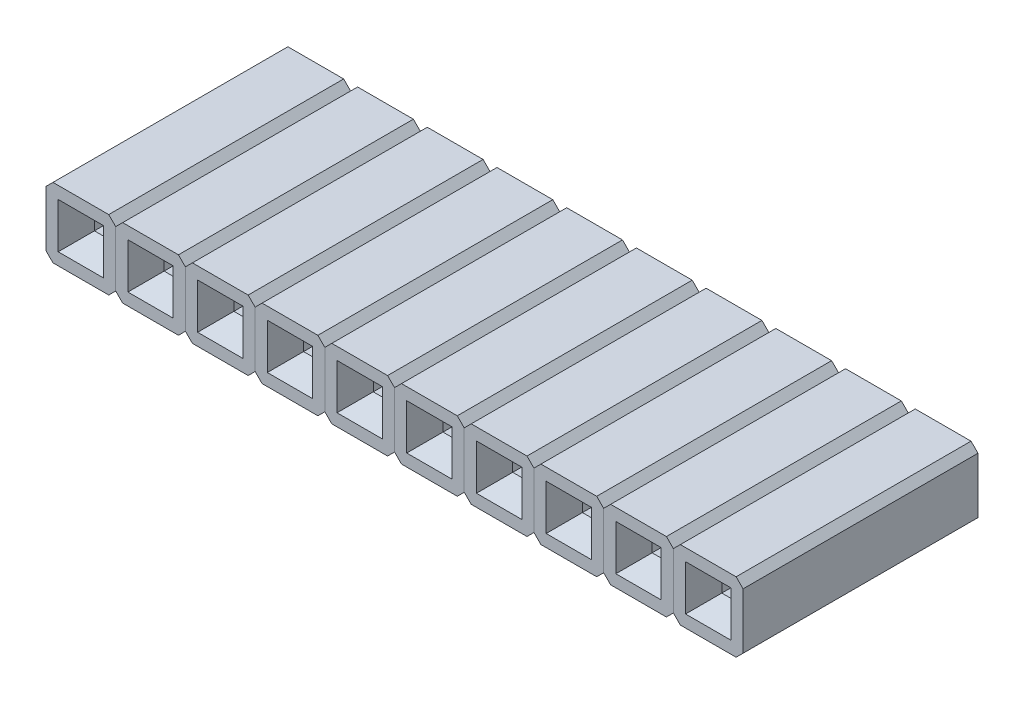
SolidWorks part; units mm, degrees
ref_plane "Front Plane" through (0, 0, 0) normal (0, 0, 1) x (1, 0, 0)
ref_plane "Top Plane" through (0, 0, 0) normal (0, 1, 0) x (1, 0, 0)
ref_plane "Right Plane" through (0, 0, 0) normal (1, 0, 0) x (0, 0, -1)
sketch "Sketch1" plane through (0, 0, 0) normal (0, 0, 1) x (1, 0, 0)
  line L1 (0, 0) -> (2.54, 0)
  line L2 (0, 0) -> (0, 2.54)
  line L3 (0, 2.54) -> (2.54, 2.54)
  line L4 (2.54, 0) -> (2.54, 2.54)
  dimension "D1" = 2.54
  dimension "D2" = 2.54
extrude "Boss-Extrude1" add sketch "Sketch1" along normal blind 8.5598
sketch "Sketch2" plane through (0, 0, 8.5598) normal (0, 0, 1) x (1, 0, 0)
  line L0 (0, 1.27) -> (2.54, 1.27) construction
  line L1 (0, 2.54) -> (0, 0) construction
  line L2 (2.54, 0) -> (2.54, 2.54) construction
  line L4 (0.9525, 0.9525) -> (1.5875, 0.9525)
  line L5 (0.9525, 0.9525) -> (0.9525, 1.5875)
  line L6 (0.9525, 1.5875) -> (1.5875, 1.5875)
  line L7 (1.5875, 0.9525) -> (1.5875, 1.5875)
  line L8 (0.9525, 0.9525) -> (1.5875, 1.5875) construction
  line L9 (0.9525, 1.5875) -> (1.5875, 0.9525) construction
  point P6 (1.27, 1.27)
  dimension "D1" = 0.635
extrude "Cut-Extrude1" cut sketch "Sketch2" against normal blind 6.35
chamfer "Chamfer1" distance 0.508 angle 58 4 edges at (0.9525, 1.27, 8.5598) (1.27, 0.9525, 8.5598) (1.5875, 1.27, 8.5598) (1.27, 1.5875, 8.5598)
chamfer "Chamfer2" distance 0.254 angle 45 4 edges at (0, 2.54, 4.2799) (2.54, 2.54, 4.2799) (2.54, 0, 4.2799) (0, 0, 4.2799)
pattern_linear "LPattern1" count 10 spacing 2.54 along (-1, 0, 0) of bodies 102
